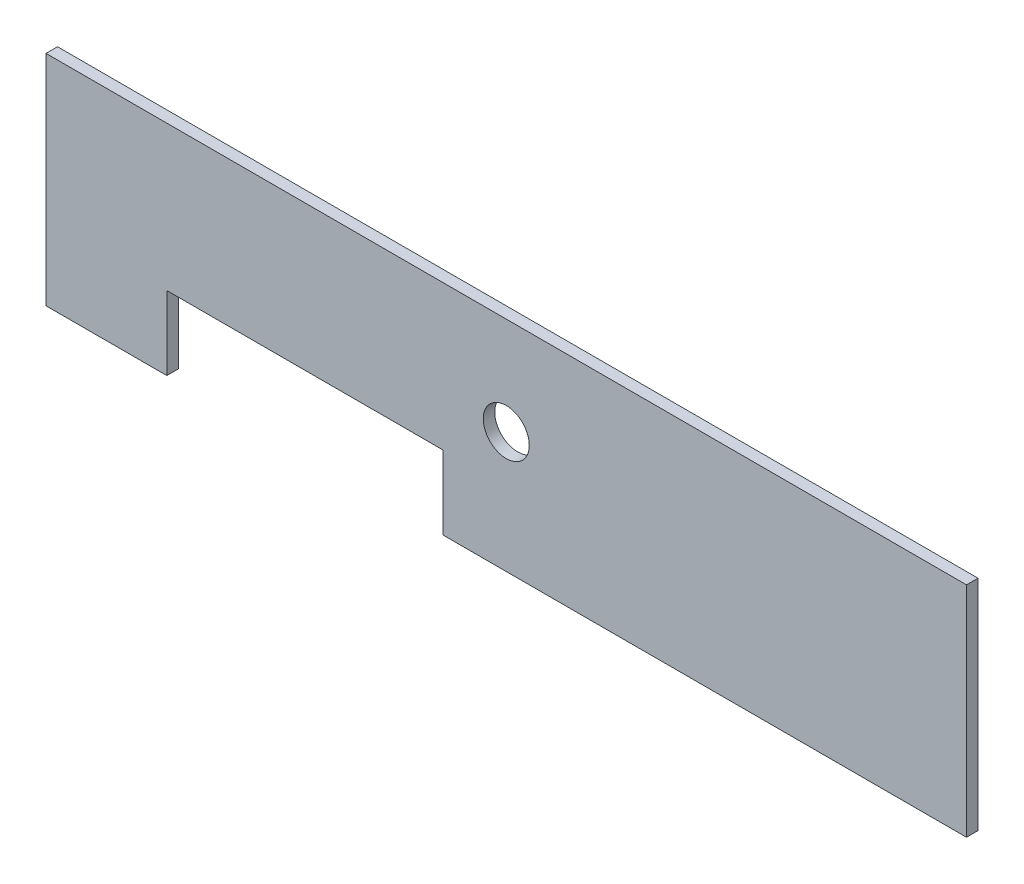
SolidWorks part; units mm, degrees
material "ABS PC"
ref_plane "前视基准面" through (0, 0, 0) normal (0, 0, 1) x (1, 0, 0)
ref_plane "上视基准面" through (0, 0, 0) normal (0, 1, 0) x (1, 0, 0)
ref_plane "右视基准面" through (0, 0, 0) normal (1, 0, 0) x (0, 0, -1)
other "Configuration Table"
sketch "草图1" plane through (0, 0, 0) normal (0, 0, 1) x (1, 0, 0)
  line L0 (-55.102, 148.5672) -> (-55.102, 53.5672) construction
  line L1 (-255.102, 148.5672) -> (144.898, 148.5672)
  line L2 (-255.102, 148.5672) -> (-255.102, 53.5672)
  line L3 (-255.102, 53.5672) -> (-202.602, 53.5672)
  line L4 (144.898, 148.5672) -> (144.898, 53.5672)
  line L5 (92.398, 53.5672) -> (144.898, 53.5672)
  line L6 (-27.602, 85.5672) -> (92.398, 85.5672) construction
  line L7 (-27.602, 85.5672) -> (-27.602, 53.5672) construction
  line L9 (92.398, 85.5672) -> (92.398, 53.5672) construction
  line L10 (-202.602, 85.5672) -> (-202.602, 53.5672)
  line L11 (-82.602, 85.5672) -> (-202.602, 85.5672)
  line L12 (-82.602, 85.5672) -> (-82.602, 53.5672)
  line L13 (-27.602, 53.5672) -> (92.398, 53.5672)
  line L14 (-82.602, 53.5672) -> (-27.602, 53.5672)
  dimension "D1" = 400
  dimension "D2" = 95
  dimension "D3" = 27.5
  dimension "D4" = 120
  dimension "D5" = 32
extrude "凸台-拉伸1" add sketch "草图1" along normal blind 5
sketch "草图2" plane through (0, 0, 5) normal (0, 0, 1) x (1, 0, 0)
  line L0 (-82.602, 53.5672) -> (144.898, 53.5672) construction
  line L1 (-55.102, 148.5672) -> (-55.102, 53.5672) construction
  line L2 (144.898, 148.5672) -> (-255.102, 148.5672) construction
  circle A0 centre (-55.102, 106.0672) radius 10
  dimension "D1" = 52.5
  dimension "D2" = 20
extrude "切除-拉伸1" cut sketch "草图2" against normal blind 10
